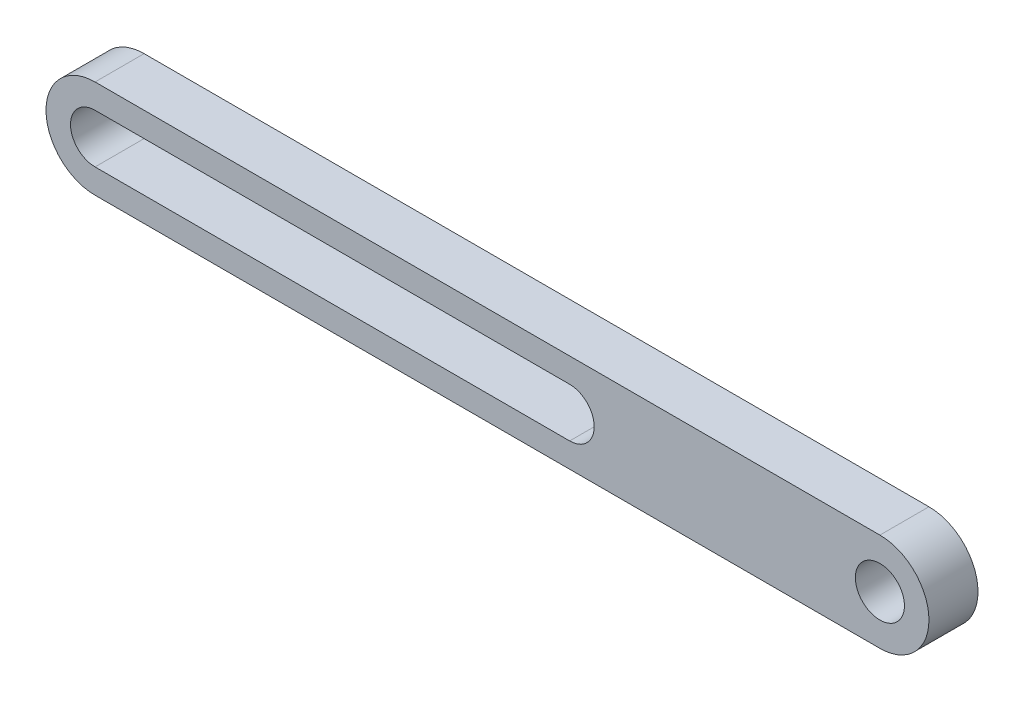
SolidWorks part; units mm, degrees
ref_plane "前视基准面" through (0, 0, 0) normal (0, 0, 1) x (1, 0, 0)
ref_plane "上视基准面" through (0, 0, 0) normal (0, 1, 0) x (1, 0, 0)
ref_plane "右视基准面" through (0, 0, 0) normal (1, 0, 0) x (0, 0, -1)
sketch "草图2" plane through (0, 0, 0) normal (0, 0, 1) x (1, 0, 0)
  line L1 (0, 0) -> (80, 0)
  line L3 (0, -10) -> (80, -10)
  arc A0 (0, 0) -> (0, -10) centre (0, -5) ccw
  arc A1 (80, -10) -> (80, 0) centre (80, -5) ccw
  point P5 (0, 0)
  dimension "D1" = 10
  dimension "D2" = 80
extrude "凸台-拉伸2" add sketch "草图2" along normal blind 5
sketch "草图3" plane through (0, 0, 5) normal (0, 0, 1) x (1, 0, 0)
  line L0 (0, -2.5) -> (48.3782, -2.5)
  line L1 (0, -7.5) -> (48.3782, -7.5)
  arc A0 (0, -2.5) -> (0, -7.5) centre (0, -5) ccw
  circle A1 centre (80, -5) radius 2.5
  arc A2 (48.3782, -7.5) -> (48.3782, -2.5) centre (48.3782, -5) ccw
  point P12 (48.3782, -5)
  dimension "D1" = 5
extrude "切除-拉伸2" cut sketch "草图3" against normal blind 15
